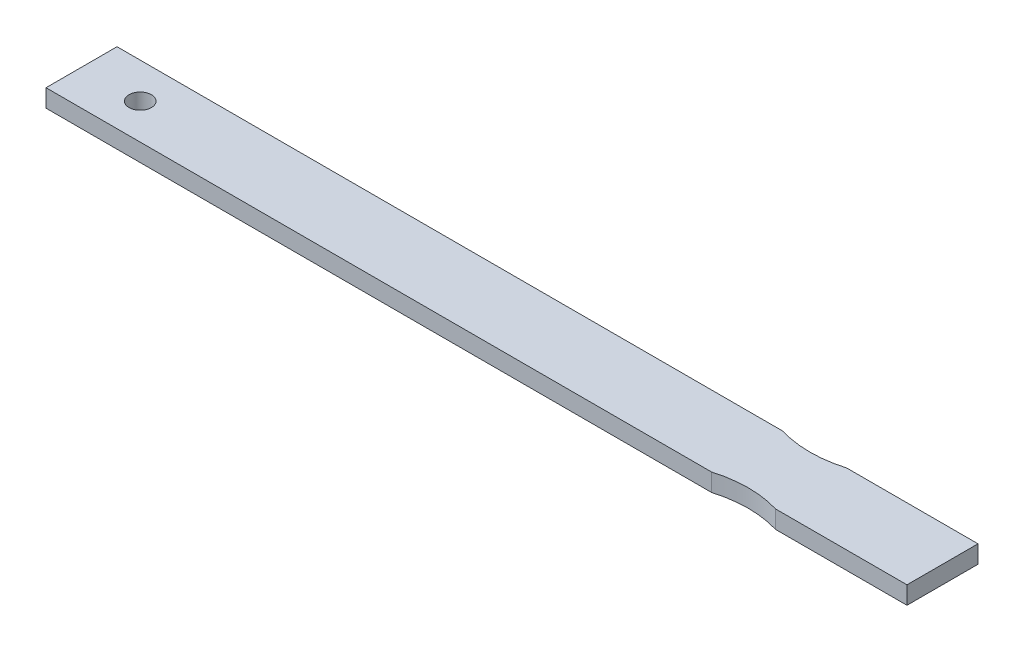
SolidWorks part; units mm, degrees
ref_plane "Front Plane" through (0, 0, 0) normal (0, 0, 1) x (1, 0, 0)
ref_plane "Top Plane" through (0, 0, 0) normal (0, 1, 0) x (1, 0, 0)
ref_plane "Right Plane" through (0, 0, 0) normal (1, 0, 0) x (0, 0, -1)
sketch "Sketch1" plane through (0, 0, 0) normal (0, 1, 0) x (1, 0, 0)
  line L0 (84.1, -12.7) -> (-153.95, -12.7)
  line L1 (153.95, -12.7) -> (106.96, -12.7)
  line L2 (153.95, -12.7) -> (153.95, 12.7)
  line L3 (153.95, 12.7) -> (106.96, 12.7)
  line L4 (-153.95, -12.7) -> (-153.95, 12.7)
  line L5 (153.95, -12.7) -> (-153.95, 12.7) construction
  line L6 (153.95, 12.7) -> (-153.95, -12.7) construction
  line L7 (0, 0) -> (153.95, 0) construction
  line L8 (84.1, 12.7) -> (-153.95, 12.7)
  arc A0 (84.1, -12.7) -> (106.96, -12.7) centre (95.53, -51.0322) cw
  arc A1 (84.1, 12.7) -> (106.96, 12.7) centre (95.53, 51.0322) ccw
  circle A2 centre (-132.95, 0) radius 4
  point P0 (0, 0)
  point P5 (106.96, -12.7)
  point P6 (84.1, -12.7)
  dimension "D5" = 40
  dimension "D6" = 21
  dimension "D7" = 8
  dimension "D1" = 25.4
  dimension "D2" = 307.9
  dimension "D3" = 46.99
  dimension "D4" = 69.85
extrude "Boss-Extrude1" add sketch "Sketch1" along normal blind 6.35
